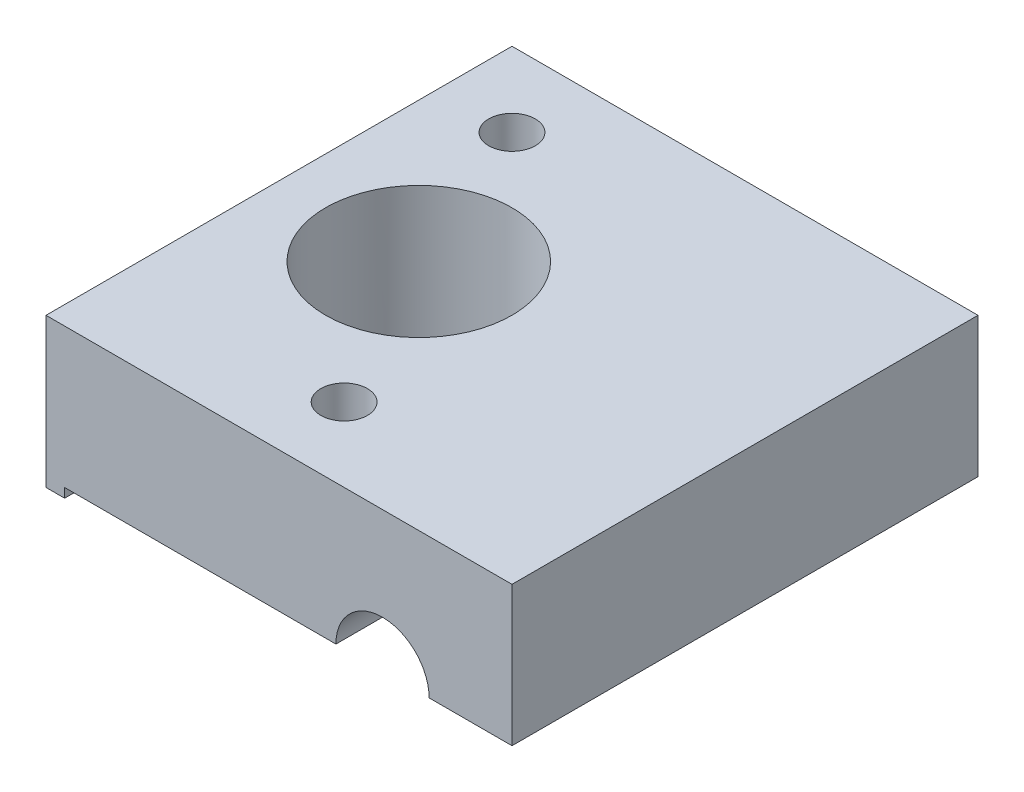
SolidWorks part; units mm, degrees
ref_plane "Plan de face" through (0, 0, 0) normal (0, 0, 1) x (1, 0, 0)
ref_plane "Plan de dessus" through (0, 0, 0) normal (0, 1, 0) x (1, 0, 0)
ref_plane "Plan de droite" through (0, 0, 0) normal (1, 0, 0) x (0, 0, -1)
sketch "Esquisse1" plane through (0, 0, 0) normal (0, 0, 1) x (1, 0, 0)
  line L0 (-36.1083, 0) -> (-36.1083, 15)
  line L1 (-36.1083, 15) -> (13.8917, 15)
  line L2 (13.8917, 15) -> (13.8917, 0)
  line L3 (13.8917, 0) -> (5, 0)
  line L4 (-5, 0) -> (-36.1083, 0)
  line L5 (-36.1083, -1) -> (-36.1083, -16) construction
  circle A0 centre (0, 0) radius 5 construction
  arc A1 (5, 0) -> (-5, 0) centre (0, 0) ccw
  dimension "D1" = 50
  dimension "D2" = 15
extrude "Boss.-Extru.1" add sketch "Esquisse1" along normal blind 50
hole_wizard "Trou taraudé M61" positions "Esquisse3" profile "Esquisse2" tap size "M6" standard "Iso" end condition through all
sketch "Esquisse3" plane through (0, 0, 0) normal (0, -1, 0) x (-1, 0, 0)
  point P0 (12.056, -42.0658)
  point P2 (28.1083, -8)
sketch "Esquisse2" plane through (-12.056, 0, 42.0658) normal (1, 0, 0) x (0, 0, -1)
  line L0 (0, 0) -> (0, 15)
  line L1 (0, 15) -> (2.5, 15)
  line L2 (2.5, 15) -> (2.5, 0)
  line L5 (2.5, 0) -> (0, 0)
  line L11 (0, -6.35) -> (0, 107.95) construction
  dimension "Diamètre du trou pour taraudage jusqu'au prochain" = 5
  dimension "Profondeur du trou pour taraudage jusqu'au prochain" = 15
cosmetic thread "Filetage de perçage1" parameters "D2"=6
cosmetic thread "Filetage de perçage2" parameters "D2"=6
sketch "Esquisse4" plane through (0, 0, 0) normal (0, -1, 0) x (1, 0, 0)
  line L0 (-36.1083, 0) -> (-5, 0) construction
  line L1 (-36.1083, 50) -> (-34.1083, 50)
  line L2 (-36.1083, 50) -> (-36.1083, 0)
  line L3 (-36.1083, 0) -> (-34.1083, 0)
  line L4 (-34.1083, 50) -> (-34.1083, 0)
  dimension "D1" = 2
extrude "Boss.-Extru.2" add sketch "Esquisse4" along normal blind 1
sketch "Esquisse5" plane through (0, 15, 0) normal (0, 1, 0) x (1, 0, 0)
  line L0 (-36.1083, -50) -> (-36.1083, 0) construction
  line L1 (13.8917, 0) -> (-36.1083, 0) construction
  circle A0 centre (-21.1083, -25) radius 10
  dimension "D1" = 20
  dimension "D2" = 15
  dimension "D3" = 25
extrude "Enlèv. mat.-Extru.1" cut sketch "Esquisse5" against normal through all contours A0
